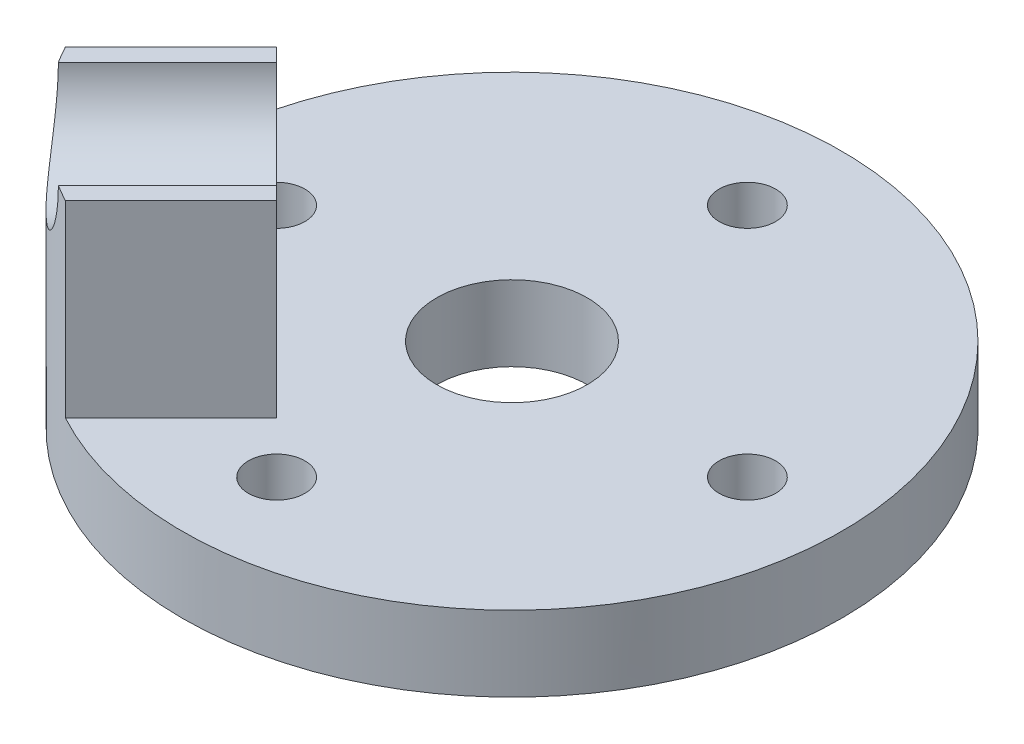
SolidWorks part; units mm, degrees
ref_plane "Front Plane" through (0, 0, 0) normal (0, 0, 1) x (1, 0, 0)
ref_plane "Top Plane" through (0, 0, 0) normal (0, 1, 0) x (1, 0, 0)
ref_plane "Right Plane" through (0, 0, 0) normal (1, 0, 0) x (0, 0, -1)
sketch "Sketch1" plane through (0, 0, 0) normal (0, 1, 0) x (1, 0, 0)
  circle A0 centre (0, 0) radius 4
  circle A1 centre (0, 0) radius 17.5
  circle A2 centre (0, 0) radius 12.5
  circle A3 centre (-12.5, 0) radius 1.5
  circle A4 centre (0, 12.5) radius 1.5
  circle A5 centre (12.5, 0) radius 1.5
  circle A6 centre (0, -12.5) radius 1.5
  dimension "D1" = 25
  dimension "D2" = 35
  dimension "D3" = 8
  dimension "D4" = 3
extrude "Boss-Extrude1" add sketch "Sketch1" along normal blind 4 contours A1 A6 A2 A3 A4 A5 | A6 A2 A5 A4 A3 A0
sketch "Sketch2" plane through (0, 4, 0) normal (0, 1, 0) x (1, 0, 0)
  line L0 (-12.5, 0) -> (0, -12.5)
  line L1 (-6.25, -6.25) -> (-2.7145, -9.7855)
  line L2 (-2.7145, -9.7855) -> (-9.7855, -2.7145)
  line L3 (-9.7855, -2.7145) -> (-15.3941, -8.323)
  line L4 (-2.7145, -9.7855) -> (-8.323, -15.3941)
  circle A0 centre (0, 0) radius 17.5 construction
  circle M5 centre (0, 0) radius 17.5
extrude "Boss-Extrude2" add sketch "Sketch2" along normal blind 10 contours L4 L0 L3 M5
sketch "Sketch3" plane through (-6.25, 0, 6.25) normal (0.7071, 0, -0.7071) x (-0.7071, 0, -0.7071)
  line L0 (5, 14) -> (-5, 14) construction
  circle A0 centre (0, 14) radius 4
extrude "Cut-Extrude1" cut sketch "Sketch3" against normal blind 10
sketch "Sketch4" plane through (-6.25, 0, 6.25) normal (0.7071, 0, -0.7071) x (-0.7071, 0, -0.7071)
  line L0 (0, 14) -> (0, 18)
  line L1 (0, 18) -> (0, 16.5)
  line L3 (-0.5, 14) -> (0.5, 14)
  line L4 (-0.5, 14) -> (-0.5, 22)
  line L5 (-0.5, 22) -> (0.5, 22)
  line L6 (0.5, 14) -> (0.5, 22)
  line L7 (-0.5, 14) -> (0.5, 22) construction
  line L8 (-0.5, 22) -> (0.5, 14) construction
  circle A0 centre (0, 14) radius 4
  circle A1 centre (0, 14) radius 7.5
  dimension "D1" = 15
